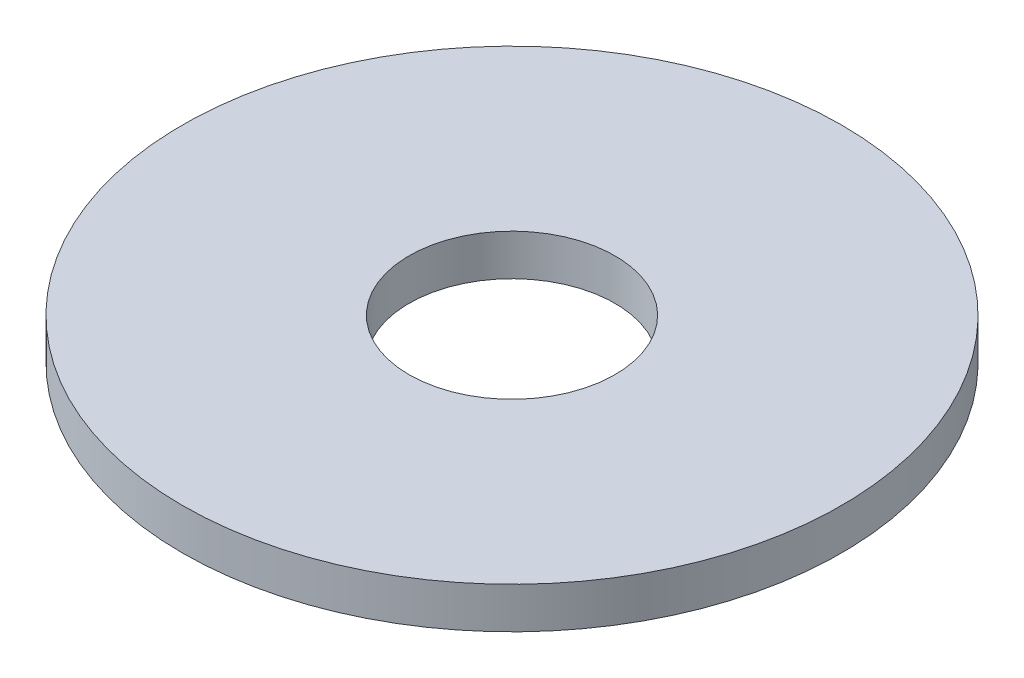
SolidWorks part; units mm, degrees
ref_plane "Front Plane" through (0, 0, 0) normal (0, 0, 1) x (1, 0, 0)
ref_plane "Top Plane" through (0, 0, 0) normal (0, 1, 0) x (1, 0, 0)
ref_plane "Right Plane" through (0, 0, 0) normal (1, 0, 0) x (0, 0, -1)
sketch "Sketch1" plane through (0, 0, 0) normal (0, 1, 0) x (1, 0, 0)
  circle A0 centre (0, 0) radius 2.125
  circle A1 centre (0, 0) radius 8
extrude "Boss-Extrude1" add sketch "Sketch1" along normal blind 1
sketch "Sketch2" plane through (0, 1, 0) normal (0, 1, 0) x (1, 0, 0)
  circle A0 centre (0, 0) radius 2.5
extrude "Cut-Extrude1" cut sketch "Sketch2" against normal blind 10
